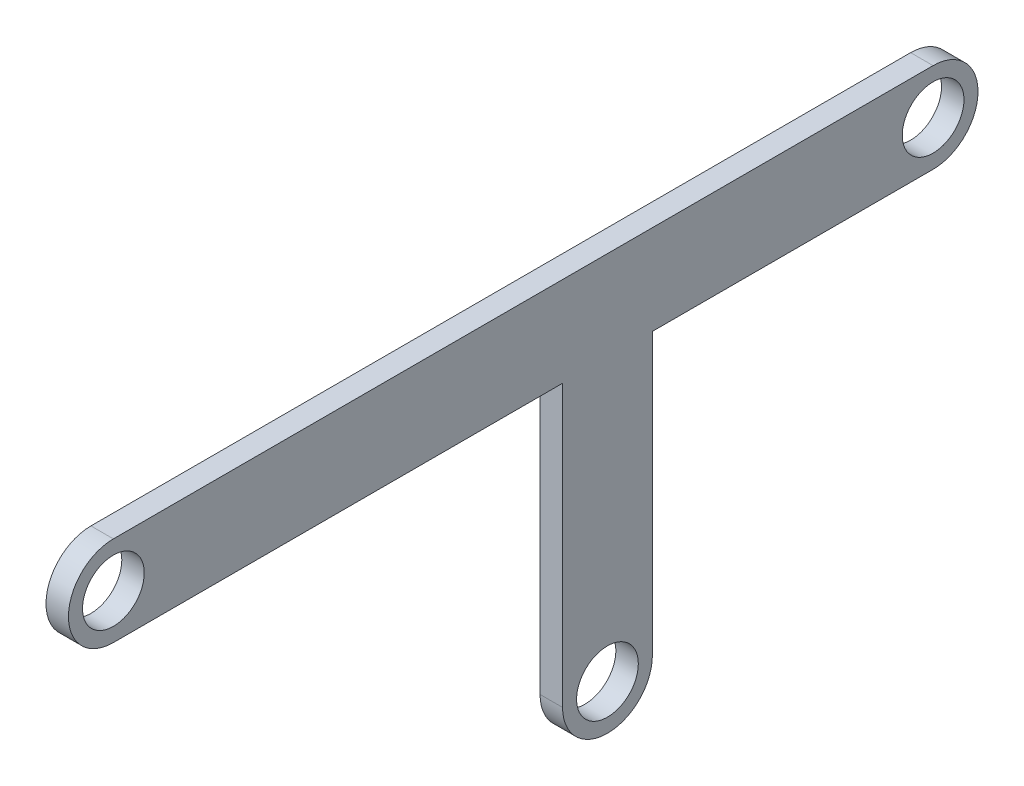
SolidWorks part; units mm, degrees
ref_plane "Front Plane" through (0, 0, 0) normal (0, 0, 1) x (1, 0, 0)
ref_plane "Top Plane" through (0, 0, 0) normal (0, 1, 0) x (1, 0, 0)
ref_plane "Right Plane" through (0, 0, 0) normal (1, 0, 0) x (0, 0, -1)
sketch "Sketch1" plane through (0, 0, 0) normal (1, 0, 0) x (0, 0, -1)
  line L0 (77, 4) -> (52, 4) construction
  line L1 (4, 4) -> (44, 4)
  line L3 (4, 12) -> (77, 12)
  line L7 (44, 4) -> (44, -21)
  line L9 (52, 4) -> (52, -21)
  line L10 (48, -25) -> (48, -18.25) construction
  line L12 (74.25, 8) -> (70, 8) construction
  line L14 (52, 4) -> (77, 4)
  circle A0 centre (4, 8) radius 2.75
  circle A1 centre (77, 8) radius 2.75
  circle A2 centre (48, -21) radius 2.75
  arc A3 (4, 12) -> (4, 4) centre (4, 8) ccw
  arc A4 (77, 4) -> (77, 12) centre (77, 8) ccw
  arc A5 (44, -21) -> (52, -21) centre (48, -21) ccw
  dimension "D6" = 5.5
  dimension "D7" = 5.5
  dimension "D8" = 5.5
  dimension "D10" = 1.25
  dimension "D1" = 8
  dimension "D4" = 4
  dimension "D2" = 25
  dimension "D3" = 40
  dimension "D5" = 8
  dimension "D9" = 33
extrude "Boss-Extrude1" add sketch "Sketch1" against normal blind 2
